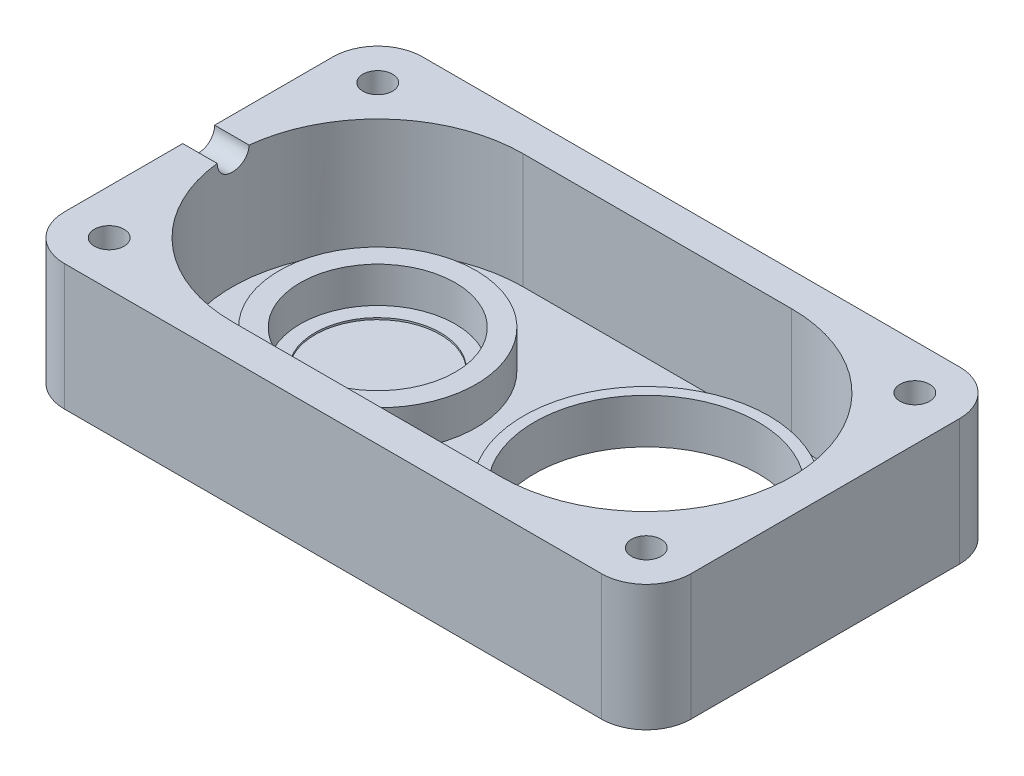
SolidWorks part; units mm, degrees
ref_plane "Front Plane" through (0, 0, 0) normal (0, 0, 1) x (1, 0, 0)
ref_plane "Top Plane" through (0, 0, 0) normal (0, 1, 0) x (1, 0, 0)
ref_plane "Right Plane" through (0, 0, 0) normal (1, 0, 0) x (0, 0, -1)
sketch "Sketch1" plane through (0, 0, 0) normal (0, 1, 0) x (1, 0, 0)
  line L0 (38.1, 19.05) -> (38.1, 25.4) construction
  line L1 (-19.05, -25.4) -> (57.15, -25.4)
  line L2 (-25.4, -19.05) -> (-25.4, 19.05)
  line L3 (-19.05, 25.4) -> (57.15, 25.4)
  line L4 (63.5, -19.05) -> (63.5, 19.05)
  line L5 (-25.4, -25.4) -> (63.5, 25.4) construction
  line L6 (-25.4, 25.4) -> (63.5, -25.4) construction
  line L7 (57.15, 0) -> (63.5, 0) construction
  line L9 (-7.62, -11.176) -> (7.62, -11.176) construction
  line L10 (-7.62, -11.176) -> (-7.62, 11.176) construction
  line L11 (-7.62, 11.176) -> (7.62, 11.176) construction
  line L12 (7.62, -11.176) -> (7.62, 11.176) construction
  line L13 (-7.62, -11.176) -> (7.62, 11.176) construction
  line L14 (-7.62, 11.176) -> (7.62, -11.176) construction
  circle A0 centre (0, 0) radius 19.05 construction
  circle A1 centre (38.1, 0) radius 19.05 construction
  circle A2 centre (38.1, 0) radius 12.7 construction
  circle A3 centre (38.1, 0) radius 15.875
  arc A4 (-25.4, 19.05) -> (-19.05, 25.4) centre (-19.05, 19.05) cw
  arc A5 (-19.05, -25.4) -> (-25.4, -19.05) centre (-19.05, -19.05) cw
  arc A6 (57.15, -25.4) -> (63.5, -19.05) centre (57.15, -19.05) ccw
  arc A7 (57.15, 25.4) -> (63.5, 19.05) centre (57.15, 19.05) cw
  circle A8 centre (-19.05, 19.05) radius 2.1
  circle A9 centre (-19.05, -19.05) radius 2.1
  circle A10 centre (57.15, -19.05) radius 2.1
  circle A11 centre (57.15, 19.05) radius 2.1
  point P6 (19.05, 0)
  dimension "D1" = 38.1
  dimension "D2" = 38.1
  dimension "D3" = 50.8
  dimension "D7" = 25.4
  dimension "D8" = 31.75
  dimension "D9" = 6.35
  dimension "D10" = 4.2
  dimension "D4" = 88.9
  dimension "D5" = 15.24
  dimension "D6" = 22.352
extrude "Boss-Extrude1" add sketch "Sketch1" along normal blind 17.8791
sketch "Sketch2" plane through (0, 17.8791, 0) normal (0, 1, 0) x (1, 0, 0)
  line L0 (0, 20.6375) -> (38.1, 20.6375)
  line L1 (38.1, -20.6375) -> (0, -20.6375)
  arc A0 (0, 20.6375) -> (0, -20.6375) centre (0, 0) ccw
  arc A1 (38.1, -20.6375) -> (38.1, 20.6375) centre (38.1, 0) ccw
  dimension "D1" = 41.275
extrude "Cut-Extrude1" cut sketch "Sketch2" against normal offset from surface (16.3551 mm away) 1.524 up to face at (57.15, 0, 21.15)
sketch "Sketch3" plane through (0, 1.524, 0) normal (0, 1, 0) x (1, 0, 0)
  circle A0 centre (0, 0) radius 13.97
  circle A1 centre (0, 0) radius 8.89
  dimension "D1" = 27.94
  dimension "D2" = 17.78
extrude "Boss-Extrude2" add sketch "Sketch3" along normal blind 0.254
sketch "Sketch4" plane through (0, 1.778, 0) normal (0, 1, 0) x (1, 0, 0)
  circle A0 centre (0, 0) radius 10.9995
  circle A1 centre (0, 0) radius 13.97 construction
  circle A2 centre (0, 0) radius 13.97
  dimension "D1" = 21.9989
extrude "Boss-Extrude3" add sketch "Sketch4" along normal blind 5.08
sketch "Sketch5" plane through (0, 1.524, 0) normal (0, 1, 0) x (1, 0, 0)
  circle A0 centre (38.1, 0) radius 17.399
  circle A1 centre (38.1, 0) radius 15.875 construction
  circle A2 centre (38.1, 0) radius 15.875
  dimension "D1" = 1.524
extrude "Boss-Extrude4" add sketch "Sketch5" along normal blind 4.826
sketch "Sketch6" plane through (-25.4, 0, 0) normal (-1, 0, 0) x (0, 0, 1)
  line L0 (-19.05, 17.8791) -> (19.05, 17.8791) construction
  circle A0 centre (0, 17.8791) radius 2.2606
  dimension "D1" = 4.5212
extrude "Cut-Extrude2" cut sketch "Sketch6" against normal up to next
sketch "Sketch7" plane through (0, 0, 0) normal (0, -1, 0) x (1, 0, 0)
  circle A0 centre (-19.05, 19.05) radius 3.75
  circle A1 centre (-19.05, -19.05) radius 3.75
  circle A2 centre (57.15, -19.05) radius 3.75
  circle A3 centre (57.15, 19.05) radius 3.75
  dimension "D1" = 7.5
extrude "Cut-Extrude3" cut sketch "Sketch7" against normal blind 4.5
